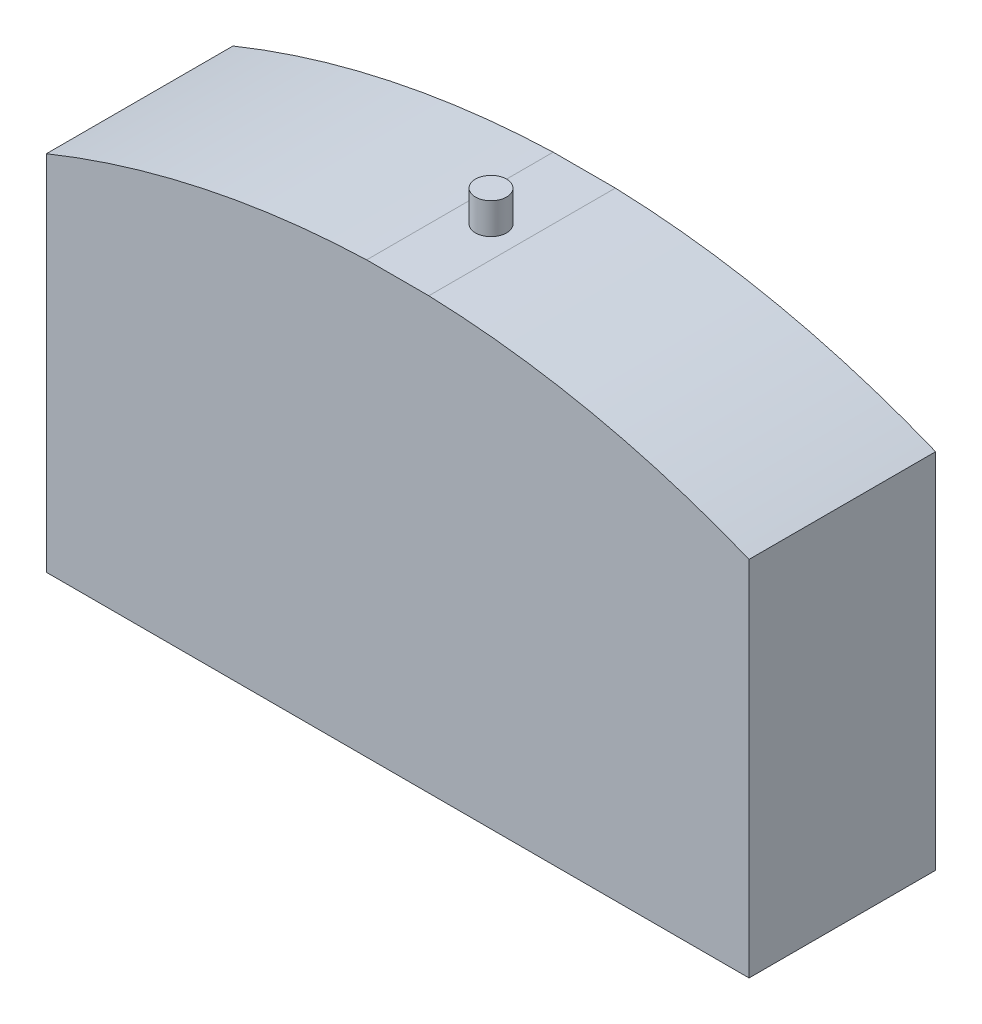
SolidWorks part; units mm, degrees
ref_plane "Front Plane" through (0, 0, 0) normal (0, 0, 1) x (1, 0, 0)
ref_plane "Top Plane" through (0, 0, 0) normal (0, 1, 0) x (1, 0, 0)
ref_plane "Right Plane" through (0, 0, 0) normal (1, 0, 0) x (0, 0, -1)
sketch "Sketch1" plane through (0, 0, 0) normal (0, 0, 1) x (1, 0, 0)
  line L0 (0, 0) -> (0, 149.9166) construction
  line L1 (-5, 149.9166) -> (5, 149.9166)
  line L3 (-56.5, 138.9523) -> (-56.5, 80.6523)
  line L4 (-56.5, 80.6523) -> (56.5, 80.6523)
  line L5 (56.5, 138.9523) -> (56.5, 80.6523)
  arc A0 (56.5, 138.9523) -> (5, 149.9166) centre (0, 0) ccw
  arc A1 (-5, 149.9166) -> (-56.5, 138.9523) centre (0, 0) ccw
  dimension "D1" = 300
  dimension "D2" = 113
  dimension "D3" = 58.3
  dimension "D4" = 10
extrude "Boss-Extrude1" add sketch "Sketch1" along normal blind 30
sketch "Sketch2" plane through (0, 0, 0) normal (0, 0, -1) x (-1, 0, 0)
  line L8 (4.9497, 146.9166) -> (-4.9497, 146.9166)
  line L9 (-53.5, 136.9188) -> (-53.5, 83.6523)
  line L10 (-53.5, 83.6523) -> (53.5, 83.6523)
  line L11 (53.5, 83.6523) -> (53.5, 136.9188)
  line L12 (4.9497, 146.9166) -> (-4.9497, 146.9166)
  line L13 (-53.5, 136.9188) -> (-53.5, 83.6523)
  line L14 (-53.5, 83.6523) -> (53.5, 83.6523)
  line L15 (53.5, 83.6523) -> (53.5, 136.9188)
  arc A4 (53.5, 136.9188) -> (4.9497, 146.9166) centre (0, 0) ccw
  arc A5 (-4.9497, 146.9166) -> (-53.5, 136.9188) centre (0, 0) ccw
  arc A6 (53.5, 136.9188) -> (4.9497, 146.9166) centre (0, 0) ccw
  arc A7 (-4.9497, 146.9166) -> (-53.5, 136.9188) centre (0, 0) ccw
  dimension "D1" = 3
extrude "Cut-Extrude1" cut sketch "Sketch2" against normal blind 27
sketch "Sketch3" plane through (0, 149.9166, 0) normal (0, 1, 0) x (1, 0, 0)
  line L0 (0, 0) -> (0, -30) construction
  line L1 (5, -30) -> (-5, -30) construction
  line L2 (-5, -15) -> (5, -15) construction
  line L3 (-5, -30) -> (-5, 0) construction
  line L4 (5, -30) -> (5, 0) construction
  circle A0 centre (0, -15) radius 2.5
  dimension "D1" = 5
extrude "Boss-Extrude2" add sketch "Sketch3" along normal blind 5
